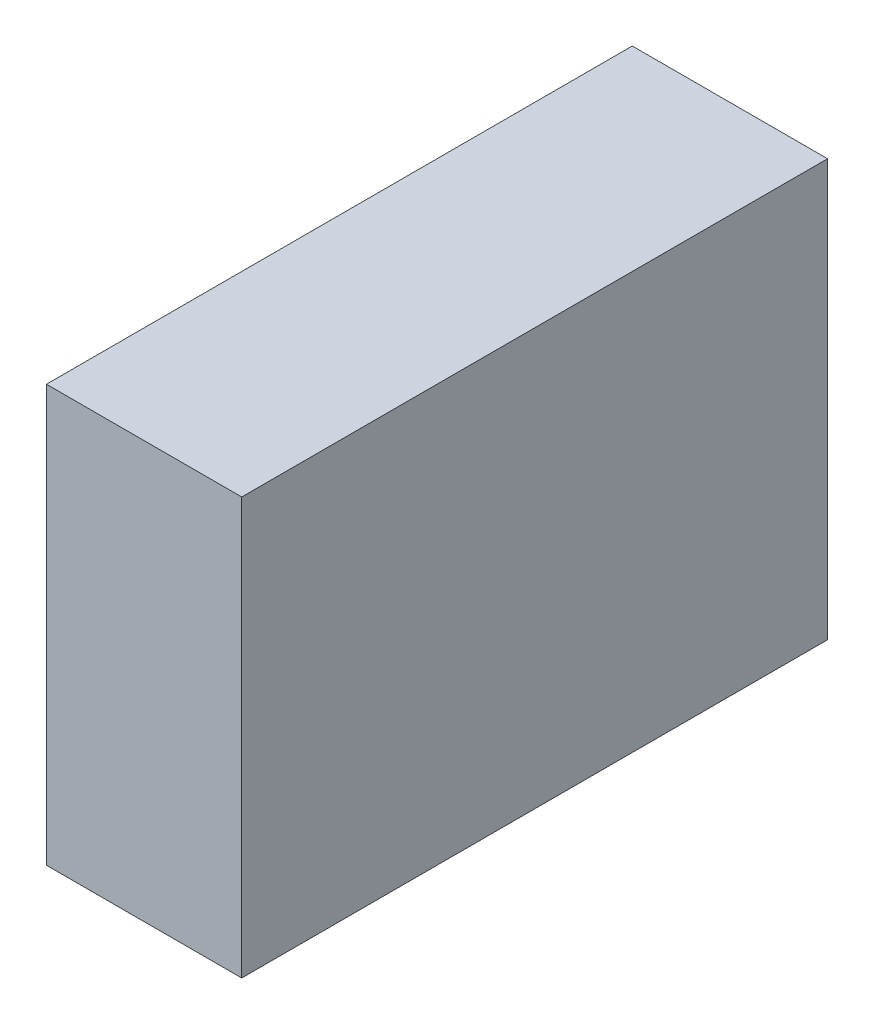
SolidWorks part; units mm, degrees
ref_plane "Front Plane" through (0, 0, 0) normal (0, 0, 1) x (1, 0, 0)
ref_plane "Top Plane" through (0, 0, 0) normal (0, 1, 0) x (1, 0, 0)
ref_plane "Right Plane" through (0, 0, 0) normal (1, 0, 0) x (0, 0, -1)
sketch "Sketch1" plane through (0, 0, 0) normal (1, 0, 0) x (0, 0, -1)
  line L1 (-22.5, -16) -> (22.5, -16)
  line L2 (-22.5, -16) -> (-22.5, 16)
  line L3 (-22.5, 16) -> (22.5, 16)
  line L4 (22.5, -16) -> (22.5, 16)
  line L5 (-22.5, -16) -> (22.5, 16) construction
  line L6 (-22.5, 16) -> (22.5, -16) construction
  point P0 (0, 0)
  dimension "D1" = 45
  dimension "D2" = 32
extrude "Boss-Extrude1" add sketch "Sketch1" along normal blind 15
